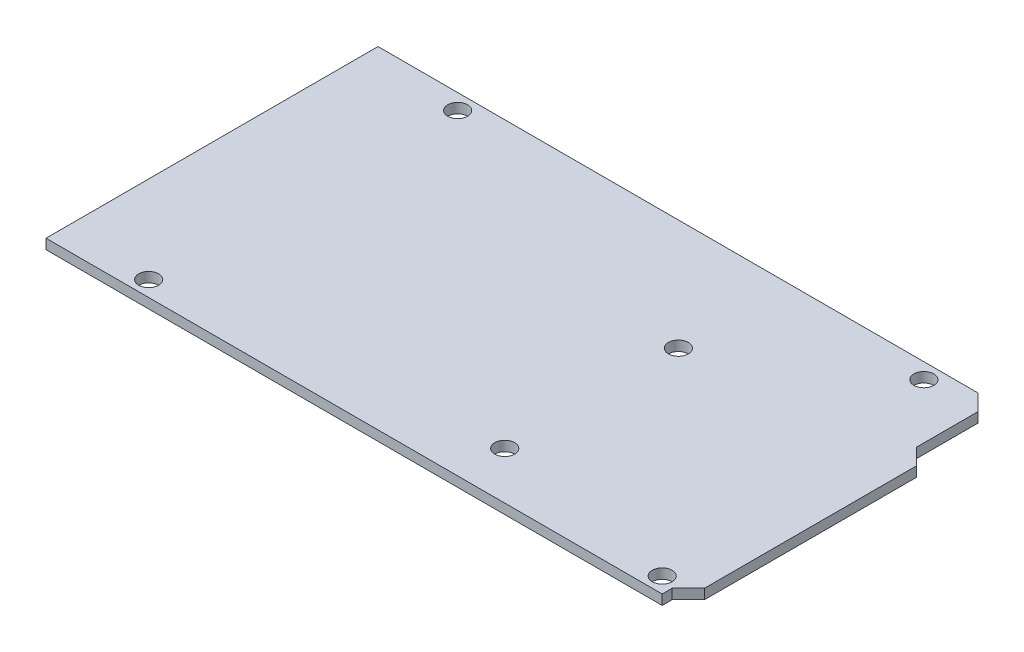
SolidWorks part; units mm, degrees
ref_plane "Front Plane" through (0, 0, 0) normal (0, 0, 1) x (1, 0, 0)
ref_plane "Top Plane" through (0, 0, 0) normal (0, 1, 0) x (1, 0, 0)
ref_plane "Right Plane" through (0, 0, 0) normal (1, 0, 0) x (0, 0, -1)
sketch "Sketch2" plane through (0, 0, 0) normal (0, 1, 0) x (1, 0, 0)
  line L0 (50.8, -22.47) -> (50.8, 11.5869)
  line L1 (48.2, -26.67) -> (-50.8, -26.67)
  line L2 (45.6, 26.67) -> (-50.8, 26.67)
  line L3 (-50.8, -26.67) -> (-50.8, 26.67)
  line L4 (50.8, -26.67) -> (-50.8, 26.67) construction
  line L5 (0, 0) -> (-50.8, -26.67) construction
  line L6 (48.2, 24.07) -> (48.2, 14.1869)
  line L8 (50.8, 11.5869) -> (48.2, 14.1869)
  line L9 (45.6, 26.67) -> (48.2, 24.07)
  line L12 (48.2, -25.07) -> (50.8, -22.47)
  line L13 (48.2, -25.07) -> (48.2, -26.67)
  point P1 (0, 0)
  dimension "D1" = 101.6
  dimension "D2" = 53.34
  dimension "D3" = 99
  dimension "D4" = 1.6
  dimension "D5" = 135
  dimension "D6" = 2.6
  dimension "D7" = 2.6
  dimension "D8" = 45
extrude "Boss-Extrude1" add sketch "Sketch2" along normal blind 1.6
sketch "Esboço1" plane through (0, 1.6, 0) normal (0, 1, 0) x (1, 0, 0)
  line L0 (-50.8, 26.67) -> (-50.8, -26.67) construction
  line L2 (-50.8, -26.67) -> (48.2, -26.67) construction
  line L3 (45.6, 26.67) -> (-50.8, 26.67) construction
  line L4 (48.2, -26.67) -> (48.2, -25.07) construction
  line L5 (15.3, 8.83) -> (15.3, -18.7805) construction
  circle A0 centre (-35.5, 24.17) radius 1.6
  circle A1 centre (-36.8, -24.17) radius 1.6
  circle A2 centre (39.4, 24.17) radius 1.6
  circle A3 centre (45.7, -24.17) radius 1.6
  circle A4 centre (15.3, 8.83) radius 1.6
  circle A5 centre (15.3, -19.07) radius 1.6
  dimension "D1" = 3.2
  dimension "D2" = 15.3
  dimension "D3" = 2.5
  dimension "D4" = 14
  dimension "D5" = 2.5
  dimension "D6" = 2.5
  dimension "D7" = 74.9
  dimension "D8" = 2.5
  dimension "D9" = 2.5
  dimension "D10" = 50.8
  dimension "D11" = 27.9
  dimension "D12" = 7.6
extrude "Corte-extrusão1" cut sketch "Esboço1" against normal blind 10
